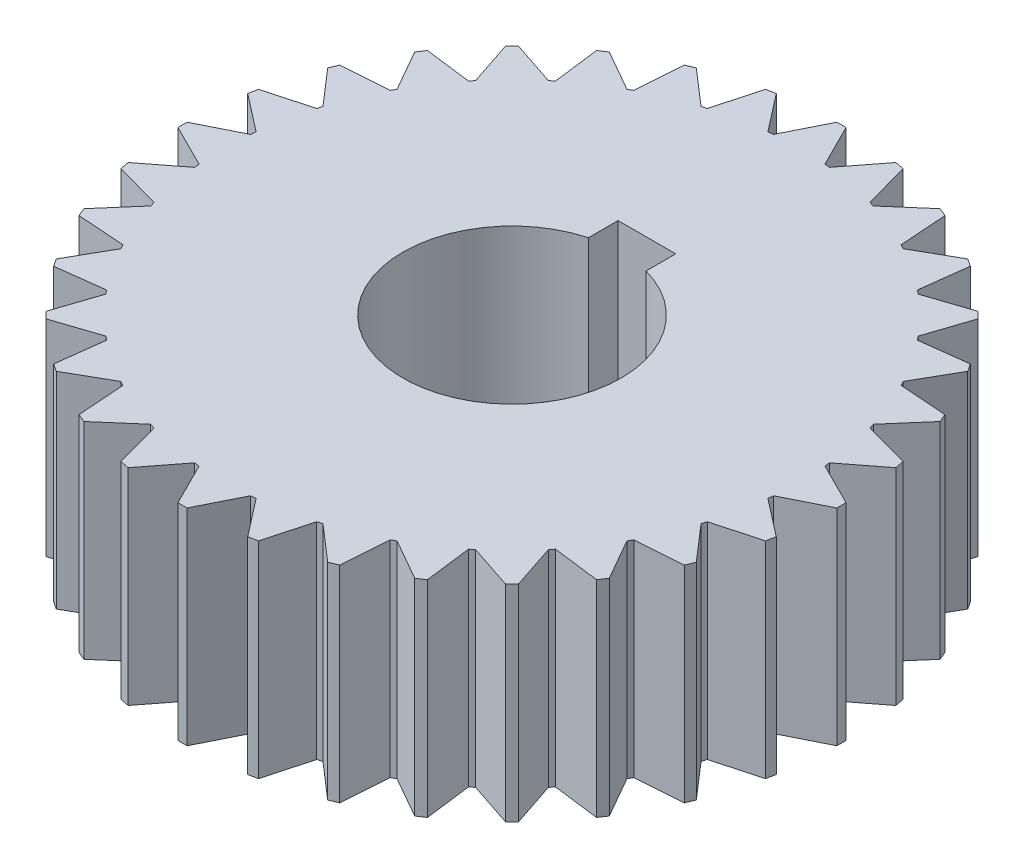
SolidWorks part; units mm, degrees
ref_plane "Front Plane" through (0, 0, 0) normal (0, 0, 1) x (1, 0, 0)
ref_plane "Top Plane" through (0, 0, 0) normal (0, 1, 0) x (1, 0, 0)
ref_plane "Right Plane" through (0, 0, 0) normal (1, 0, 0) x (0, 0, -1)
sketch "Sketch1" plane through (0, 0, 0) normal (0, 1, 0) x (1, 0, 0)
  line L1 (0, 20.884) -> (-1.5875, 17.709)
  line L2 (0, 20.884) -> (1.5875, 17.709)
  line L4 (4.0743, 20.4827) -> (1.8979, 17.6784)
  line L5 (4.0743, 20.4827) -> (5.0118, 17.059)
  line L6 (7.992, 19.2943) -> (5.3103, 16.9685)
  line L7 (7.992, 19.2943) -> (8.2436, 15.7535)
  line L8 (11.6025, 17.3644) -> (8.5186, 15.6065)
  line L9 (11.6025, 17.3644) -> (11.1585, 13.8425)
  line L10 (14.7672, 14.7672) -> (11.3996, 13.6447)
  line L11 (14.7672, 14.7672) -> (13.6447, 11.3996)
  line L12 (17.3644, 11.6025) -> (13.8425, 11.1585)
  line L13 (17.3644, 11.6025) -> (15.6065, 8.5186)
  line L14 (19.2943, 7.992) -> (15.7535, 8.2436)
  line L15 (19.2943, 7.992) -> (16.9685, 5.3103)
  line L16 (20.4827, 4.0743) -> (17.059, 5.0118)
  line L17 (20.4827, 4.0743) -> (17.6784, 1.8979)
  line L18 (20.884, 0) -> (17.709, 1.5875)
  line L19 (20.884, 0) -> (17.709, -1.5875)
  line L20 (20.4827, -4.0743) -> (17.6784, -1.8979)
  line L21 (20.4827, -4.0743) -> (17.059, -5.0118)
  line L22 (19.2943, -7.992) -> (16.9685, -5.3103)
  line L23 (19.2943, -7.992) -> (15.7535, -8.2436)
  line L24 (17.3644, -11.6025) -> (15.6065, -8.5186)
  line L25 (17.3644, -11.6025) -> (13.8425, -11.1585)
  line L26 (14.7672, -14.7672) -> (13.6447, -11.3996)
  line L27 (14.7672, -14.7672) -> (11.3996, -13.6447)
  line L28 (11.6025, -17.3644) -> (11.1585, -13.8425)
  line L29 (11.6025, -17.3644) -> (8.5186, -15.6065)
  line L30 (7.992, -19.2943) -> (8.2436, -15.7535)
  line L31 (7.992, -19.2943) -> (5.3103, -16.9685)
  line L32 (4.0743, -20.4827) -> (5.0118, -17.059)
  line L33 (4.0743, -20.4827) -> (1.8979, -17.6784)
  line L34 (0, -20.884) -> (1.5875, -17.709)
  line L35 (0, -20.884) -> (-1.5875, -17.709)
  line L36 (-4.0743, -20.4827) -> (-1.8979, -17.6784)
  line L37 (-4.0743, -20.4827) -> (-5.0118, -17.059)
  line L38 (-7.992, -19.2943) -> (-5.3103, -16.9685)
  line L39 (-7.992, -19.2943) -> (-8.2436, -15.7535)
  line L40 (-11.6025, -17.3644) -> (-8.5186, -15.6065)
  line L41 (-11.6025, -17.3644) -> (-11.1585, -13.8425)
  line L42 (-14.7672, -14.7672) -> (-11.3996, -13.6447)
  line L43 (-14.7672, -14.7672) -> (-13.6447, -11.3996)
  line L44 (-17.3644, -11.6025) -> (-13.8425, -11.1585)
  line L45 (-17.3644, -11.6025) -> (-15.6065, -8.5186)
  line L46 (-19.2943, -7.992) -> (-15.7535, -8.2436)
  line L47 (-19.2943, -7.992) -> (-16.9685, -5.3103)
  line L48 (-20.4827, -4.0743) -> (-17.059, -5.0118)
  line L49 (-20.4827, -4.0743) -> (-17.6784, -1.8979)
  line L50 (-20.884, 0) -> (-17.709, -1.5875)
  line L51 (-20.884, 0) -> (-17.709, 1.5875)
  line L52 (-20.4827, 4.0743) -> (-17.6784, 1.8979)
  line L53 (-20.4827, 4.0743) -> (-17.059, 5.0118)
  line L54 (-19.2943, 7.992) -> (-16.9685, 5.3103)
  line L55 (-19.2943, 7.992) -> (-15.7535, 8.2436)
  line L56 (-17.3644, 11.6025) -> (-15.6065, 8.5186)
  line L57 (-17.3644, 11.6025) -> (-13.8425, 11.1585)
  line L58 (-14.7672, 14.7672) -> (-13.6447, 11.3996)
  line L59 (-14.7672, 14.7672) -> (-11.3996, 13.6447)
  line L60 (-11.6025, 17.3644) -> (-11.1585, 13.8425)
  line L61 (-11.6025, 17.3644) -> (-8.5186, 15.6065)
  line L62 (-7.992, 19.2943) -> (-8.2436, 15.7535)
  line L63 (-7.992, 19.2943) -> (-5.3103, 16.9685)
  line L64 (-4.0743, 20.4827) -> (-5.0118, 17.059)
  line L65 (-4.0743, 20.4827) -> (-1.8979, 17.6784)
  arc A0 (-1.5875, 17.709) -> (-1.8979, 17.6784) centre (0, 0) ccw
  arc A1 (-5.0118, 17.059) -> (-5.3103, 16.9685) centre (0, 0) ccw
  arc A2 (-8.2436, 15.7535) -> (-8.5186, 15.6065) centre (0, 0) ccw
  arc A3 (-11.1585, 13.8425) -> (-11.3996, 13.6447) centre (0, 0) ccw
  arc A4 (-13.6447, 11.3996) -> (-13.8425, 11.1585) centre (0, 0) ccw
  arc A5 (-15.6065, 8.5186) -> (-15.7535, 8.2436) centre (0, 0) ccw
  arc A6 (-16.9685, 5.3103) -> (-17.059, 5.0118) centre (0, 0) ccw
  arc A7 (-17.6784, 1.8979) -> (-17.709, 1.5875) centre (0, 0) ccw
  arc A8 (-17.709, -1.5875) -> (-17.6784, -1.8979) centre (0, 0) ccw
  arc A9 (-17.059, -5.0118) -> (-16.9685, -5.3103) centre (0, 0) ccw
  arc A10 (-15.7535, -8.2436) -> (-15.6065, -8.5186) centre (0, 0) ccw
  arc A11 (-13.8425, -11.1585) -> (-13.6447, -11.3996) centre (0, 0) ccw
  arc A12 (-11.3996, -13.6447) -> (-11.1585, -13.8425) centre (0, 0) ccw
  arc A13 (-8.5186, -15.6065) -> (-8.2436, -15.7535) centre (0, 0) ccw
  arc A14 (-5.3103, -16.9685) -> (-5.0118, -17.059) centre (0, 0) ccw
  arc A15 (-1.8979, -17.6784) -> (-1.5875, -17.709) centre (0, 0) ccw
  arc A16 (1.5875, -17.709) -> (1.8979, -17.6784) centre (0, 0) ccw
  arc A17 (5.0118, -17.059) -> (5.3103, -16.9685) centre (0, 0) ccw
  arc A18 (8.2436, -15.7535) -> (8.5186, -15.6065) centre (0, 0) ccw
  arc A19 (11.1585, -13.8425) -> (11.3996, -13.6447) centre (0, 0) ccw
  arc A20 (13.6447, -11.3996) -> (13.8425, -11.1585) centre (0, 0) ccw
  arc A21 (15.6065, -8.5186) -> (15.7535, -8.2436) centre (0, 0) ccw
  arc A22 (16.9685, -5.3103) -> (17.059, -5.0118) centre (0, 0) ccw
  arc A23 (17.6784, -1.8979) -> (17.709, -1.5875) centre (0, 0) ccw
  arc A24 (17.709, 1.5875) -> (17.6784, 1.8979) centre (0, 0) ccw
  arc A25 (17.059, 5.0118) -> (16.9685, 5.3103) centre (0, 0) ccw
  arc A26 (15.7535, 8.2436) -> (15.6065, 8.5186) centre (0, 0) ccw
  arc A27 (13.8425, 11.1585) -> (13.6447, 11.3996) centre (0, 0) ccw
  arc A28 (11.3996, 13.6447) -> (11.1585, 13.8425) centre (0, 0) ccw
  arc A29 (8.5186, 15.6065) -> (8.2436, 15.7535) centre (0, 0) ccw
  arc A30 (5.3103, 16.9685) -> (5.0118, 17.059) centre (0, 0) ccw
  arc A31 (1.8979, 17.6784) -> (1.5875, 17.709) centre (0, 0) ccw
  dimension "D1" = 35.56
  dimension "D2" = 3.175
  dimension "D4" = 32
extrude "Boss-Extrude1" add sketch "Sketch1" along normal blind 12.7
sketch "Sketch2" plane through (0, 12.7, 0) normal (0, 1, 0) x (1, 0, 0)
  circle A0 centre (0, 0) radius 20.32
  dimension "D1" = 40.64
extrude "Cut-Extrude1" cut sketch "Sketch2" against normal through all flip side to cut
sketch "Sketch3" plane through (0, 12.7, 0) normal (0, 1, 0) x (1, 0, 0)
  line L0 (0, 0) -> (0, 6.731) construction
  line L2 (-1.778, 8.3185) -> (1.778, 8.3185)
  line L3 (-1.778, 8.3185) -> (-1.778, 5.1435)
  line L4 (-1.778, 5.1435) -> (1.778, 5.1435)
  line L5 (1.778, 8.3185) -> (1.778, 5.1435)
  line L6 (-1.778, 8.3185) -> (1.778, 5.1435) construction
  line L7 (-1.778, 5.1435) -> (1.778, 8.3185) construction
  circle A0 centre (0, 0) radius 6.731
  dimension "D1" = 13.462
  dimension "D2" = 3.556
  dimension "D3" = 3.175
extrude "Cut-Extrude3" cut sketch "Sketch3" against normal through all contours L3 A0 L5 L4 | L5 A0 L3 L4 | A0 L5 L2 L3
